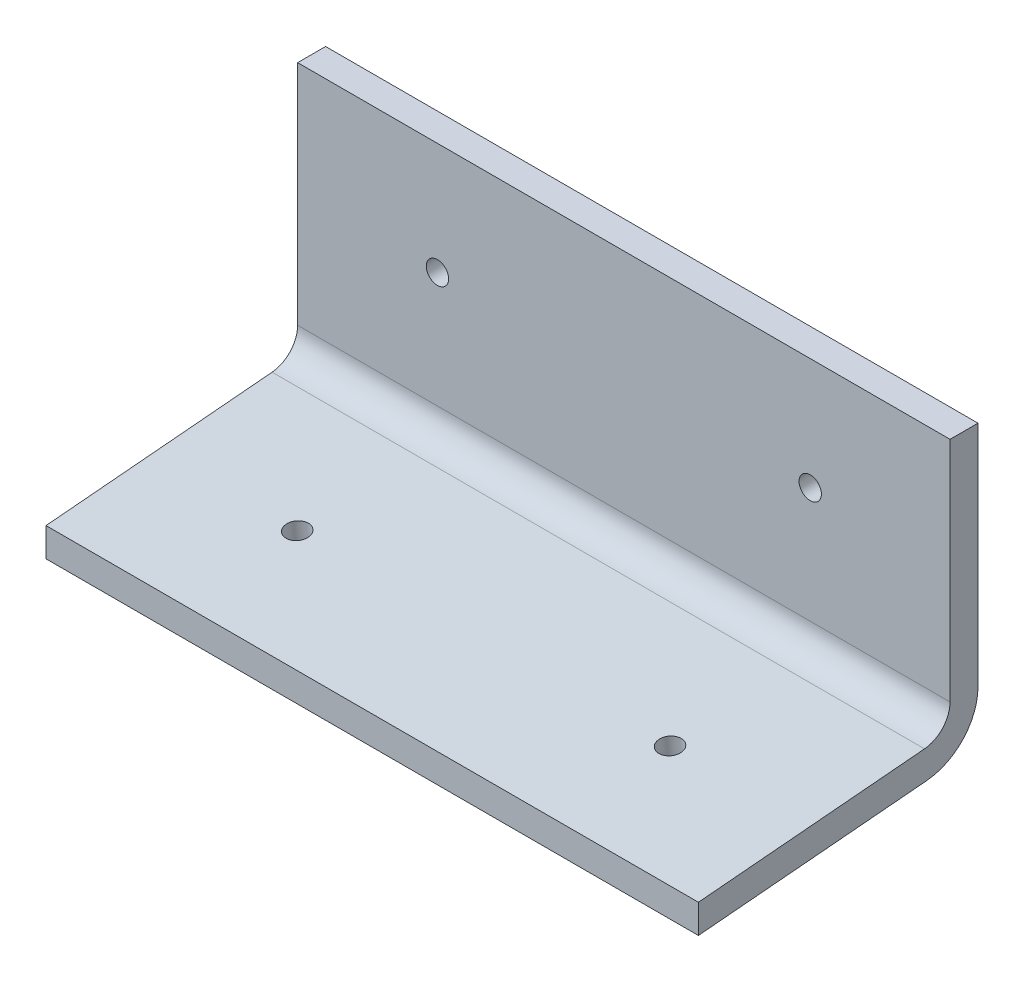
SolidWorks part; units mm, degrees
material "Silicon Rubber"
ref_plane "Front" through (0, 0, 0) normal (0, 0, 1) x (1, 0, 0)
ref_plane "Top" through (0, 0, 0) normal (0, 1, 0) x (1, 0, 0)
ref_plane "Right" through (0, 0, 0) normal (1, 0, 0) x (0, 0, -1)
sketch "Sketch11" plane through (0, 0, 0) normal (1, 0, 0) x (0, 0, -1)
  line L0 (0, 0) -> (0, -31.0964)
  line L1 (-6.9559, -38.6874) -> (-38.1, -41.4122)
  line L2 (-7.2879, -34.7907) -> (-38.1, -37.4864)
  line L3 (-3.81, 0) -> (-3.81, -30.9952)
  line L4 (-3.81, 0) -> (0, 0)
  line L5 (-38.1, -41.4122) -> (-38.1, -37.4864)
  arc A2 (-6.9559, -38.6874) -> (0, -31.0964) centre (-7.62, -31.0964) ccw
  arc A3 (-7.2879, -34.7907) -> (-3.81, -30.9952) centre (-7.62, -30.9952) ccw
  point P11 (0, -15.5482)
  point P12 (-1.905, 0)
  dimension "D6" = 7.62
  dimension "D7" = 3.81
  dimension "D1" = 3.9108
  dimension "D2" = 3.81
  dimension "D3" = 38.1
  dimension "D4" = 38.1
  dimension "D5" = 95
extrude "Boss-Extrude1" add sketch "Sketch11" along normal blind 88.9 contours A2 L0 L4 L3 A3 L2 L5 L1
sketch "Sketch12" plane through (0, -33.8937, -2.9653) normal (0, 0.9962, 0.0872) x (1, 0, 0)
  line L0 (44.45, -36.3553) -> (44.45, 32.5863) construction
  line L2 (88.9, -41.2222) -> (0, -41.2222) construction
  line L3 (0, -10.2924) -> (0, -41.2222) construction
  circle A0 centre (19.05, -25.9822) radius 1.524
  circle A1 centre (69.85, -25.9822) radius 1.524
  point P3 (44.45, -41.2222)
  point P12 (69.85, -25.9822)
  point P14 (19.05, -25.9822)
  dimension "D1" = 3.048
  dimension "D2" = 15.24
  dimension "D3" = 19.05
sketch "Sketch13" plane through (0, 0, 3.81) normal (0, 0, 1) x (1, 0, 0)
  line L0 (0, 0) -> (0, -30.9952) construction
  line L1 (88.9, 0) -> (0, 0) construction
  line L2 (44.45, 0) -> (44.45, -46.1582) construction
  circle A0 centre (19.05, -15.24) radius 1.524
  circle A1 centre (69.85, -15.24) radius 1.524
  point P7 (44.45, 0)
  point P12 (19.05, -15.24)
  point P13 (69.85, -15.24)
  dimension "D1" = 3.048
  dimension "D2" = 19.05
  dimension "D3" = 15.24
extrude "Cut-Extrude1" cut sketch "Sketch13" against normal blind 88.9 contours A1 | A0
extrude "Cut-Extrude2" cut sketch "Sketch12" against normal blind 88.9 contours A1 | A0
